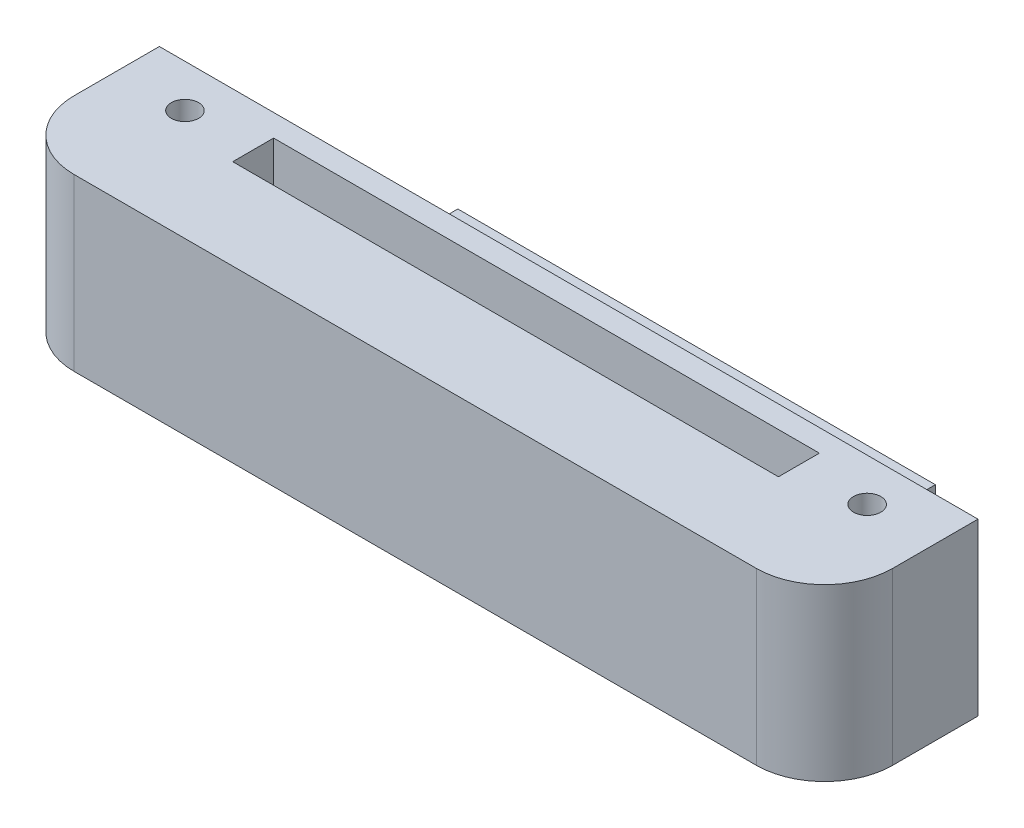
SolidWorks part; units mm, degrees
ref_plane "Front Plane" through (0, 0, 0) normal (0, 0, 1) x (1, 0, 0)
ref_plane "Top Plane" through (0, 0, 0) normal (0, 1, 0) x (1, 0, 0)
ref_plane "Right Plane" through (0, 0, 0) normal (1, 0, 0) x (0, 0, -1)
sketch "Sketch1" plane through (0, 0, 0) normal (0, 1, 0) x (1, 0, 0)
  line L1 (-60, -15.625) -> (60, -15.625)
  line L2 (-60, -15.625) -> (-60, 15.625)
  line L3 (-60, 15.625) -> (60, 15.625)
  line L4 (60, -15.625) -> (60, 15.625)
  line L5 (-60, -15.625) -> (60, 15.625) construction
  line L6 (-60, 15.625) -> (60, -15.625) construction
  point P0 (0, 0)
  dimension "D1" = 31.25
  dimension "D2" = 120
extrude "Boss-Extrude1" add sketch "Sketch1" along normal blind 25
sketch "Sketch2" plane through (60, 0, 0) normal (1, 0, 0) x (0, 0, -1)
  line L1 (15.625, 25) -> (-3.125, 25)
  line L2 (15.625, 25) -> (15.625, 7.5)
  line L3 (15.625, 7.5) -> (-3.125, 7.5)
  line L4 (-3.125, 25) -> (-3.125, 7.5)
  dimension "D1" = 17.5
  dimension "D2" = 18.75
extrude "Cut-Extrude1" cut sketch "Sketch2" against normal through all
hole_wizard "Ø4.0mm Dowel Hole1" positions "Sketch3" profile "Sketch4" hole size "Ø4.0" standard "ANSI Metric" end condition through all
sketch "Sketch3" plane through (0, 25, 0) normal (0, 1, 0) x (1, 0, 0)
  line L1 (0, -3.125) -> (0, -15.625) construction
  line L2 (-60, -3.125) -> (60, -3.125) construction
  line L3 (-60, -15.625) -> (60, -15.625) construction
  point P0 (50, -9.375)
  point P2 (-50, -9.375)
  dimension "D1" = 100
  dimension "D2" = 50
  dimension "D3" = 6.25
  dimension "D4" = 6.25
sketch "Sketch4" plane through (50, 25, 9.375) normal (1, 0, 0) x (0, 0, 1)
  line L0 (0, 0) -> (0, 25)
  line L1 (0, 25) -> (2, 25)
  line L2 (2, 25) -> (2, 0)
  line L5 (2, 0) -> (0, 0)
  line L11 (0, -6.35) -> (0, 107.95) construction
  dimension "Thru Hole Dia." = 4
  dimension "Thru Hole Depth" = 25
sketch "Sketch5" plane through (0, 0, 15.625) normal (0, 0, 1) x (1, 0, 0)
  line L1 (-60, 0) -> (60, 0)
  line L2 (-60, 0) -> (-60, 25)
  line L3 (-60, 25) -> (60, 25)
  line L4 (60, 0) -> (60, 25)
extrude "Boss-Extrude2" add sketch "Sketch5" along normal blind 10
sketch "Sketch6" plane through (0, 25, 0) normal (0, 1, 0) x (1, 0, 0)
  line L0 (-60, -3.125) -> (60, -3.125) construction
  line L1 (-40, -12.375) -> (40, -12.375)
  line L2 (-40, -12.375) -> (-40, -6.375)
  line L3 (-40, -6.375) -> (40, -6.375)
  line L4 (40, -12.375) -> (40, -6.375)
  line L5 (-40, -12.375) -> (40, -6.375) construction
  line L6 (-40, -6.375) -> (40, -12.375) construction
  line L8 (60, -25.625) -> (60, -3.125) construction
  point P0 (0, -9.375)
  point P7 (0, 0)
  dimension "D2" = 60
  dimension "D1" = 6.25
  dimension "D3" = 80
  dimension "D4" = 6
extrude "Cut-Extrude2" cut sketch "Sketch6" against normal blind 17.5
fillet "Fillet1" radius 10 2 edges at (60, 12.5, 25.625) (-60, 12.5, 25.625)
sketch "Sketch7" plane through (0, 7.5, 0) normal (0, 1, 0) x (1, 0, 0)
  line L0 (-60, -3.125) -> (60, -3.125) construction
  line L1 (-60, 15.625) -> (-35, 15.625)
  line L2 (-60, 15.625) -> (-60, -3.125)
  line L3 (-60, -3.125) -> (-35, -3.125)
  line L4 (-35, 15.625) -> (-35, -3.125)
  line L5 (-60, -3.125) -> (60, -3.125) construction
  line L6 (60, 15.625) -> (35, 15.625)
  line L7 (60, 15.625) -> (60, -3.125)
  line L8 (60, -3.125) -> (35, -3.125)
  line L9 (35, 15.625) -> (35, -3.125)
  dimension "D1" = 25
  dimension "D2" = 25
extrude "Cut-Extrude3" cut sketch "Sketch7" against normal blind 25
